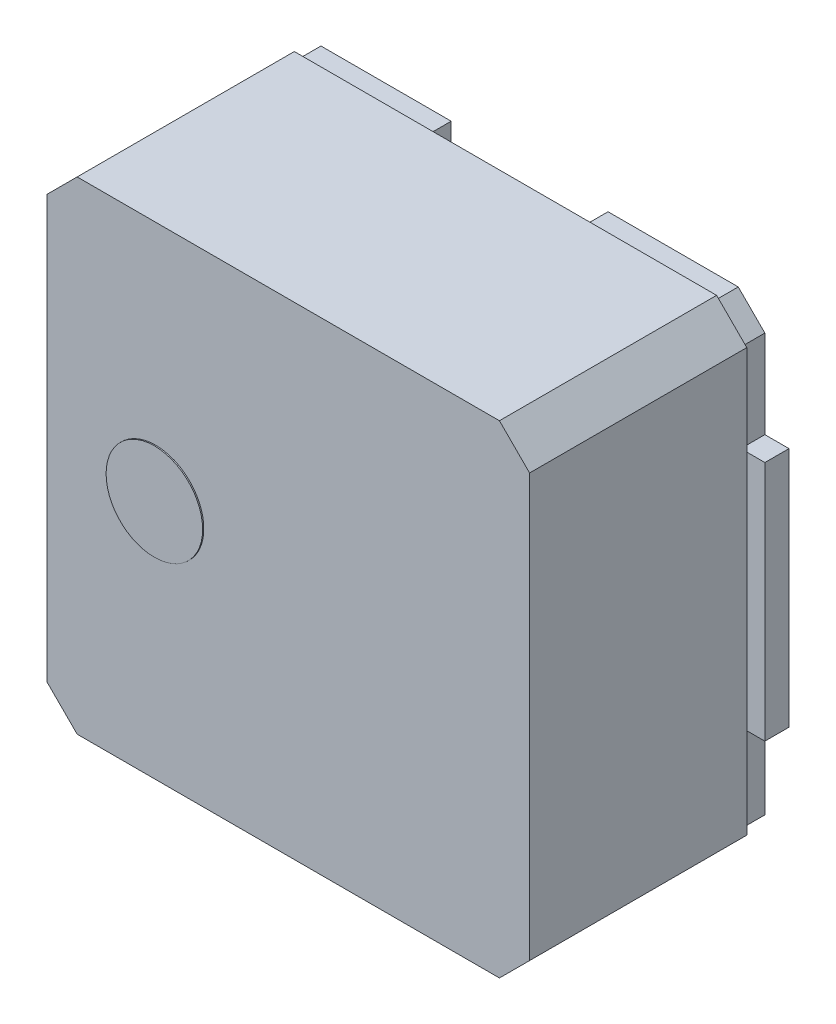
SolidWorks part; units mm, degrees
ref_plane "Plan de face" through (0, 0, 0) normal (0, 0, 1) x (1, 0, 0)
ref_plane "Plan de dessus" through (0, 0, 0) normal (0, 1, 0) x (1, 0, 0)
ref_plane "Plan de droite" through (0, 0, 0) normal (1, 0, 0) x (0, 0, -1)
sketch "Esquisse1" plane through (0, 0, 0) normal (0, 0, 1) x (1, 0, 0)
  line L0 (0, 2) -> (0, 0) construction
  line L9 (0, 0) -> (2, 0) construction
  line L10 (2, -1.75) -> (2, 1.75)
  line L11 (2, 1.75) -> (1.75, 2)
  line L12 (1.75, 2) -> (-1.75, 2)
  line L13 (-2, 1.75) -> (-1.75, 2)
  line L14 (-2, -1.75) -> (-2, 1.75)
  line L15 (-2, -1.75) -> (-1.75, -2)
  line L16 (1.75, -2) -> (-1.75, -2)
  line L17 (2, -1.75) -> (1.75, -2)
  point P2 (0, 0)
  point P9 (2.1653, 1.1846)
  point P10 (1.0634, 2.5069)
  point P14 (-2, 0)
  point P15 (2.0964, 0)
  point P18 (2, 1.2617)
  point P22 (0, 2.0964)
  dimension "D1" = 4
  dimension "D2" = 3.5
extrude "body" add sketch "Esquisse1" along normal blind 1.8 from offset 0.2
sketch "Esquisse2" plane through (0, 0, 0) normal (0, 0, 1) x (1, 0, 0)
  line L31 (0, 2) -> (0, -2) construction
  line L40 (1.75, 2) -> (-1.75, 2) construction
  line L41 (-1.75, -2) -> (1.75, -2) construction
  line L44 (2, -1.75) -> (2, 1.75) construction
  line L63 (-2, 0) -> (2, 0) construction
  line L64 (-2, 1.75) -> (-2, -1.75) construction
  line L75 (0.65, 1.95) -> (0.65, -1.95)
  line L76 (-0.65, 1.95) -> (-0.65, -1.95)
  line L77 (-0.65, 1.95) -> (-1.7293, 1.95)
  line L78 (0.65, -1.95) -> (1.7293, -1.95)
  line L79 (1.95, 1) -> (2.15, 1)
  line L80 (2.15, 1) -> (2.15, -1)
  line L81 (2.15, -1) -> (1.95, -1)
  line L82 (1.95, 1) -> (1.95, 1.7293)
  line L83 (1.95, 1.7293) -> (1.7293, 1.95)
  line L84 (1.7293, 1.95) -> (-1.7293, 1.95)
  line L85 (-1.7293, 1.95) -> (-1.95, 1.7293)
  line L86 (-1.95, 1.7293) -> (-1.95, -1.7293)
  line L87 (-1.95, -1.7293) -> (-1.7293, -1.95)
  line L88 (-1.7293, -1.95) -> (1.7293, -1.95)
  line L89 (1.7293, -1.95) -> (1.95, -1.7293)
  line L90 (1.95, -1.7293) -> (1.95, 1.7293)
  line L91 (1.95, 1.7293) -> (1.7293, 1.95)
  line L92 (1.7293, 1.95) -> (0.65, 1.95)
  line L93 (-1.7293, 1.95) -> (-1.95, 1.7293)
  line L94 (-1.95, 1.7293) -> (-1.95, 1)
  line L95 (-1.95, -1.7293) -> (-1.7293, -1.95)
  line L96 (-1.7293, -1.95) -> (-0.65, -1.95)
  line L97 (1.7293, -1.95) -> (1.95, -1.7293)
  line L98 (1.95, -1.7293) -> (1.95, -1)
  line L99 (-2.15, -1) -> (-1.95, -1)
  line L100 (-2.15, 1) -> (-2.15, -1)
  line L101 (-1.95, 1) -> (-2.15, 1)
  line L102 (-1.95, -1) -> (-1.95, -1.7293)
  dimension "D1" = 0.05
  dimension "D2" = 2
  dimension "D3" = 1.3
  dimension "D4" = 4.3
extrude "pins" add sketch "Esquisse2" along normal up to surface (0.2 mm away) up to face at (0, 0, 0.2)
sketch "Esquisse3" plane through (0, 0, 2) normal (0, 0, 1) x (1, 0, 0)
  circle A0 centre (-1.1, 0) radius 0.4
  dimension "D1" = 0.8
  dimension "D2" = 1.1
extrude "mark" add sketch "Esquisse3" along normal blind 0.01
